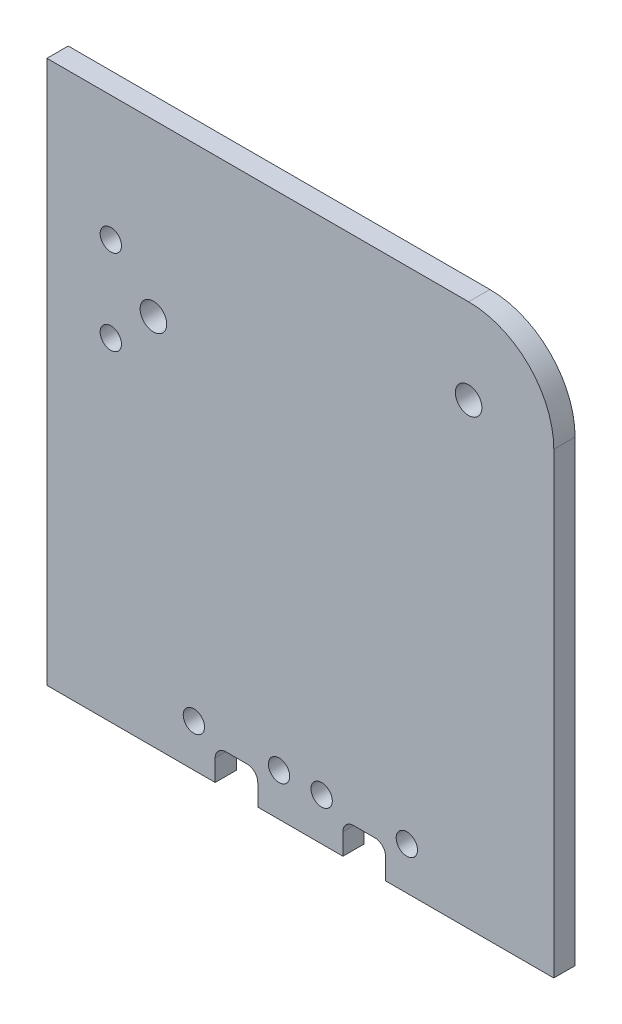
SolidWorks part; units mm, degrees
material "自訂玻璃纖維"
ref_plane "前基準面" through (0, 0, 0) normal (0, 0, 1) x (1, 0, 0)
ref_plane "上基準面" through (0, 0, 0) normal (0, 1, 0) x (1, 0, 0)
ref_plane "右基準面" through (0, 0, 0) normal (1, 0, 0) x (0, 0, -1)
sketch "草圖1" plane through (0, 0, 0) normal (0, 0, 1) x (1, 0, 0)
  line L0 (-28.5419, -5.3352) -> (-28.5419, -52.3352)
  line L1 (19.0581, -12.618) -> (19.0581, -52.618)
  line L2 (-28.5419, -52.3352) -> (-28.5419, -53.618)
  line L3 (-27.5419, -4.618) -> (11.0581, -4.618)
  line L4 (-11.7419, -52.618) -> (-9.7419, -52.618)
  line L5 (-8.7419, -55.618) -> (-0.7419, -55.618)
  line L6 (19.0581, -53.9008) -> (19.0581, -52.618)
  line L7 (-27.5419, -4.618) -> (-28.5419, -4.618)
  line L8 (-28.5419, -4.618) -> (-28.5419, -5.3352)
  line L9 (-12.7419, -53.618) -> (-12.7419, -55.618)
  line L10 (3.2581, -53.618) -> (3.2581, -55.618)
  line L11 (-8.7419, -53.618) -> (-8.7419, -55.618)
  line L12 (-28.5419, -53.618) -> (-28.5419, -55.618)
  line L13 (-28.5419, -55.618) -> (-12.7419, -55.618)
  line L14 (19.0581, -53.9008) -> (19.0581, -55.618)
  line L15 (0.2581, -52.618) -> (2.2581, -52.618)
  line L16 (-0.7419, -53.618) -> (-0.7419, -55.618)
  line L17 (3.2581, -55.618) -> (19.0581, -55.618)
  circle A0 centre (-18.5419, -20.618) radius 1.25
  circle A4 centre (-6.7419, -51.618) radius 1
  circle A5 centre (-22.5419, -16.368) radius 1
  circle A6 centre (-22.5419, -24.368) radius 1
  arc A7 (-12.7419, -53.618) -> (-11.7419, -52.618) centre (-11.7419, -53.618) cw
  arc A8 (-9.7419, -52.618) -> (-8.7419, -53.618) centre (-9.7419, -53.618) cw
  circle A9 centre (11.0581, -12.618) radius 1.25
  circle A10 centre (-14.7419, -51.618) radius 1
  circle A12 centre (5.2581, -51.618) radius 1
  circle A13 centre (-2.7419, -51.618) radius 1
  arc A14 (19.0581, -12.618) -> (11.0581, -4.618) centre (11.0581, -12.618) ccw
  arc A15 (2.2581, -52.618) -> (3.2581, -53.618) centre (2.2581, -53.618) cw
  arc A16 (-0.7419, -53.618) -> (0.2581, -52.618) centre (0.2581, -53.618) cw
  point P3 (11.0581, -12.618)
  point P19 (11.0581, -12.618)
  point P24 (-18.5419, -20.618)
  point P38 (-28.5419, -53.618)
  dimension "D3" = 2.5
  dimension "D4" = 8
  dimension "D5" = 2
  dimension "D6" = 2
  dimension "D7" = 2
  dimension "D11" = 4
  dimension "D9" = 2
  dimension "D2" = 4
extrude "填料-伸長2" add sketch "草圖1" along normal blind 2
